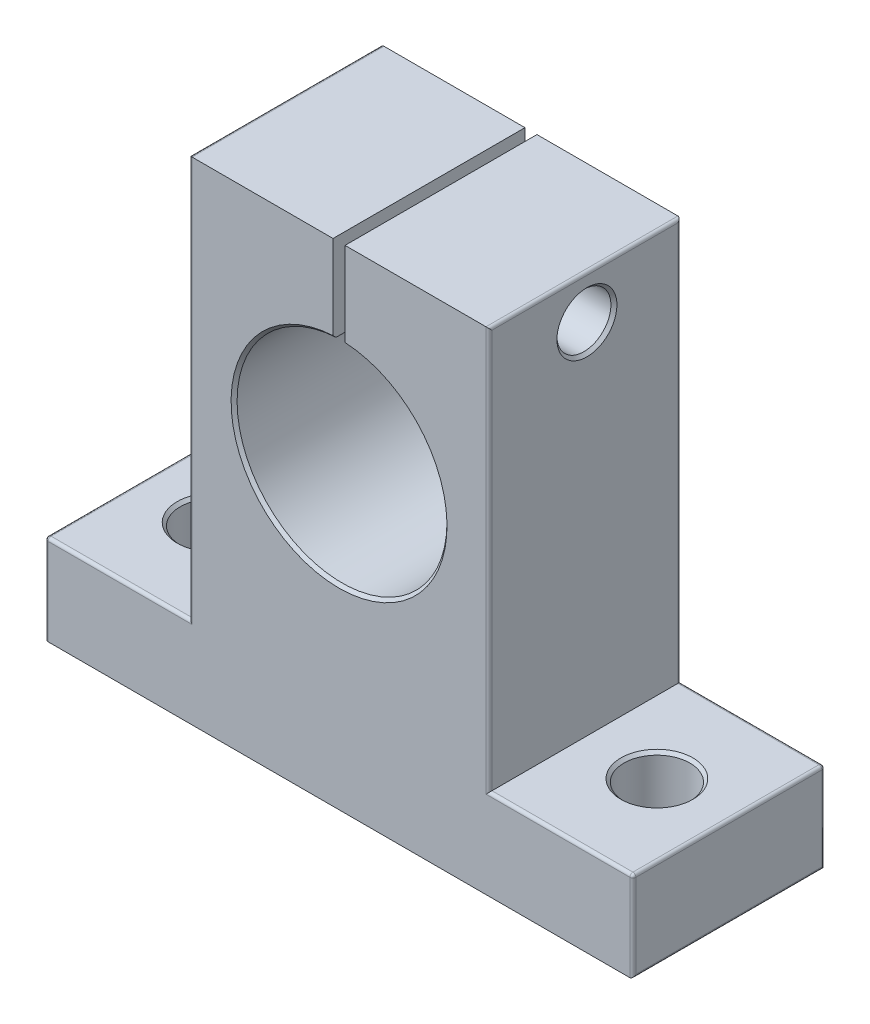
SolidWorks part; units mm, degrees
material "1060 Alloy"
ref_plane "Front Plane" through (0, 0, 0) normal (0, 0, 1) x (1, 0, 0)
ref_plane "Top Plane" through (0, 0, 0) normal (0, 1, 0) x (1, 0, 0)
ref_plane "Right Plane" through (0, 0, 0) normal (1, 0, 0) x (0, 0, -1)
sketch "Sketch1" plane through (0, 0, 0) normal (0, 0, 1) x (1, 0, 0)
  line L0 (0, 0) -> (-50000, 0) construction
  line L1 (0, 0) -> (0, 50000) construction
  line L2 (-49, -7.5) -> (-49, 7.5)
  line L3 (-49, 7.5) -> (-25, 7.5)
  line L4 (-25, 7.5) -> (-25, 74.5)
  line L5 (-25, 74.5) -> (-1, 74.5)
  line L6 (25, 74.5) -> (25, 7.5)
  line L7 (25, 7.5) -> (49, 7.5)
  line L8 (49, 7.5) -> (49, -7.5)
  line L9 (49, -7.5) -> (-49, -7.5)
  line L10 (37, -3) -> (37, 3) construction
  line L11 (-37, -3) -> (-37, 3) construction
  line L12 (-1, 74.5) -> (-1, 59.9714)
  line L13 (1, 74.5) -> (1, 59.9714)
  line L14 (1, 74.5) -> (25, 74.5)
  arc A0 (-1, 59.9714) -> (1, 59.9714) centre (0, 42.5) ccw
  point P8 (-49, 0)
  point P10 (24, -4)
  point P15 (0, -7.5)
  point P17 (0, 0)
  point P21 (37, 0)
  dimension "Shaft Diameter" = 35
  dimension "W" = 98
  dimension "P" = 50
  dimension "F" = 82
  dimension "G" = 15
  dimension "B" = 74
  dimension "D1" = 2
  dimension "h" = 50
extrude "Boss-Extrude1" add sketch "Sketch1" along normal mid plane 32
sketch "Sketch2" plane through (0, 7.5, 0) normal (0, 1, 0) x (1, 0, 0)
  line L0 (0, 0) -> (50000, 0) construction
  line L1 (0.3141, 0) -> (-49999.6859, 0) construction
  line L2 (0, 2.4842) -> (0, 50002.4842) construction
  circle A0 centre (37, 0) radius 5.5
  circle A1 centre (-37, 0) radius 5.5
  point P11 (17.1569, 0)
  dimension "B" = 74
  dimension "S" = 11
extrude "Cut-Extrude1" cut sketch "Sketch2" against normal through all
sketch "Sketch5" plane through (-1, 0, 0) normal (1, 0, 0) x (0, 0, -1)
  line L0 (-16, 67.2357) -> (16, 67.2357) construction
  line L1 (16, 59.9714) -> (16, 74.5) construction
  line L2 (0, 74.5) -> (0, 59.9714) construction
  line L3 (-16, 74.5) -> (16, 74.5) construction
  line L4 (-16, 59.9714) -> (16, 59.9714) construction
  line L5 (-16, 59.9714) -> (-16, 74.5) construction
  circle A0 centre (0.3307, 67.2357) radius 4.5
  dimension "Clamping bold" = 9
extrude "Cut-Extrude2" cut sketch "Sketch5" against normal through all both and the other way through all
chamfer "Chamfer2" distance 0.5 angle 45 6 edges at (0, 25, -16) (0, 25, 16) (-25, 67.2357, -4.8307) (-31.5, 7.5, 0) (25, 67.2357, 4.1693) (31.5, 7.5, 0)
fillet "Fillet2" radius 0.5 18 edges at (49, -7.5, 0) (49, 0, 16) (49, 7.5, 0) (49, 0, -16) (-49, 7.5, 0) (-49, 0, 16) (-49, -7.5, 0) (-49, 0, -16) (-37, 7.5, -16) (-37, 7.5, 16) (-25, 41, 16) (-25, 74.5, 0) (-25, 41, -16) (25, 41, -16) (25, 41, 16) (37, 7.5, 16) (37, 7.5, -16) (25, 74.5, 0)
equation "\"W\"= \"W@Sketch1\"'Width"
equation "\"B\"= \"B@Sketch1\"'between hold"
equation "\"F\"= \"F@Sketch1\"'Hight"
equation "\"P\"= \"P@Sketch1\""
equation "\"G\"= \"G@Sketch1\""
equation "\"Shaft diameter\"= \"Shaft Diameter@Sketch1\""
equation "\"S\" = \"S@Sketch2\"'M10"
equation "\"Clamping bold\" = 9'M8"
equation "\"h\"= \"h@Sketch1\""
